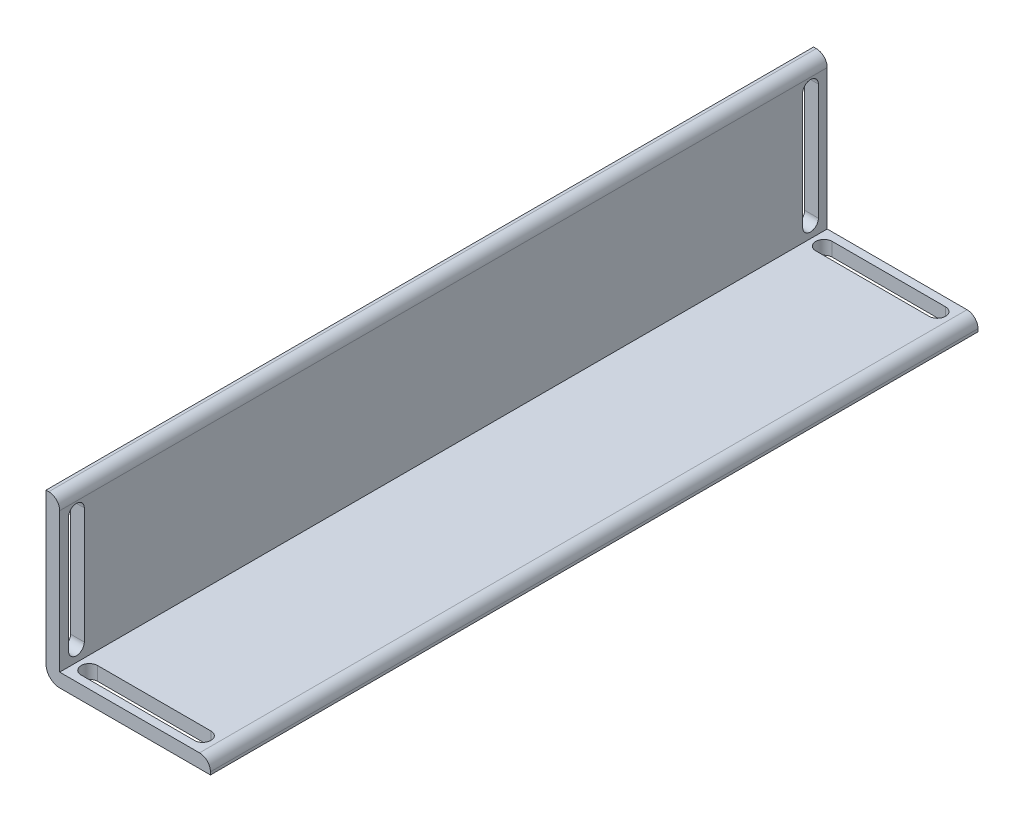
SolidWorks part; units mm, degrees
ref_plane "Front Plane" through (0, 0, 0) normal (0, 0, 1) x (1, 0, 0)
ref_plane "Top Plane" through (0, 0, 0) normal (0, 1, 0) x (1, 0, 0)
ref_plane "Right Plane" through (0, 0, 0) normal (1, 0, 0) x (0, 0, -1)
sketch "Sketch1" plane through (0, 0, 0) normal (0, 0, 1) x (1, 0, 0)
  line L0 (0, 0) -> (0, 38.1)
  line L1 (0, 38.1) -> (0.635, 38.1)
  line L2 (3.175, 35.56) -> (3.175, 3.175)
  line L3 (3.175, 3.175) -> (35.56, 3.175)
  line L4 (38.1, 0.635) -> (38.1, 0)
  line L5 (38.1, 0) -> (0, 0)
  arc A0 (38.1, 0.635) -> (35.56, 3.175) centre (35.56, 0.635) ccw
  arc A1 (3.175, 35.56) -> (0.635, 38.1) centre (0.635, 35.56) ccw
  dimension "D5" = 2.54
  dimension "D1" = 38.1
  dimension "D2" = 38.1
  dimension "D3" = 3.175
  dimension "D4" = 3.175
extrude "Boss-Extrude1" add sketch "Sketch1" along normal blind 177.8
fillet "Fillet1" radius 3.175 1 edges at (0, 0, 88.9)
sketch "Sketch2" plane through (3.175, 0, 0) normal (1, 0, 0) x (0, 0, -1)
  line L0 (-177.8, 3.175) -> (-177.8, 35.56) construction
  line L2 (-173.9293, 33.266) -> (-173.9293, 6.3572) construction
  line L3 (-172.101, 33.266) -> (-172.101, 6.3572)
  line L4 (-175.7576, 33.266) -> (-175.7576, 6.3572)
  line L5 (-88.9, 3.175) -> (-88.9, 12.7072)
  line L6 (-177.8, 3.175) -> (0, 3.175) construction
  line L7 (0, 19.3675) -> (-3.81, 19.3675)
  line L8 (-3.8707, 33.266) -> (-3.8707, 6.3572) construction
  line L9 (-5.699, 33.266) -> (-5.699, 6.3572)
  line L10 (-2.0424, 33.266) -> (-2.0424, 6.3572)
  arc A0 (-172.101, 33.266) -> (-175.7576, 33.266) centre (-173.9293, 33.266) ccw
  arc A1 (-175.7576, 6.3572) -> (-172.101, 6.3572) centre (-173.9293, 6.3572) ccw
  arc A2 (-5.699, 33.266) -> (-2.0424, 33.266) centre (-3.8707, 33.266) cw
  arc A3 (-2.0424, 6.3572) -> (-5.699, 6.3572) centre (-3.8707, 6.3572) cw
  point P0 (-173.9293, 33.266)
  point P6 (-173.9293, 19.8116)
  point P19 (-3.8707, 19.8116)
  point P24 (0, 0)
  point P25 (-173.99, 19.0572)
  point P26 (-173.99, 19.3675)
  point P27 (-173.99, 19.3675)
  point P28 (0, 0)
  point P29 (0, 0)
  point P30 (0, 0)
  point P31 (-173.99, 19.3675)
  dimension "D2" = 3.8707
  dimension "D1" = 2.0424
extrude "Cut-Extrude2" cut sketch "Sketch2" against normal blind 177.8 contours L3 A1 L4 A0 | L10 A3 L9 A2
sketch "Sketch6" plane through (0, 0, 0) normal (0, -1, 0) x (1, 0, 0)
  line L0 (35.56, 88.9) -> (11.2775, 88.9)
  line L2 (32.4903, 173.99) -> (6.232, 173.99) construction
  line L3 (32.4903, 172.085) -> (6.232, 172.085)
  line L4 (32.4903, 175.895) -> (6.232, 175.895)
  line L5 (35.56, 177.8) -> (35.56, 0) construction
  line L6 (32.4903, 3.81) -> (6.232, 3.81) construction
  line L7 (32.4903, 5.715) -> (6.232, 5.715)
  line L8 (32.4903, 1.905) -> (6.232, 1.905)
  arc A0 (32.4903, 172.085) -> (32.4903, 175.895) centre (32.4903, 173.99) ccw
  arc A1 (6.232, 175.895) -> (6.232, 172.085) centre (6.232, 173.99) ccw
  arc A2 (32.4903, 5.715) -> (32.4903, 1.905) centre (32.4903, 3.81) cw
  arc A3 (6.232, 1.905) -> (6.232, 5.715) centre (6.232, 3.81) cw
  point P6 (19.3612, 173.99)
  point P13 (19.3612, 3.81)
extrude "Cut-Extrude6" cut sketch "Sketch6" against normal blind 177.8 contours L4 A1 L3 A0 | A3 L8 A2 L7
